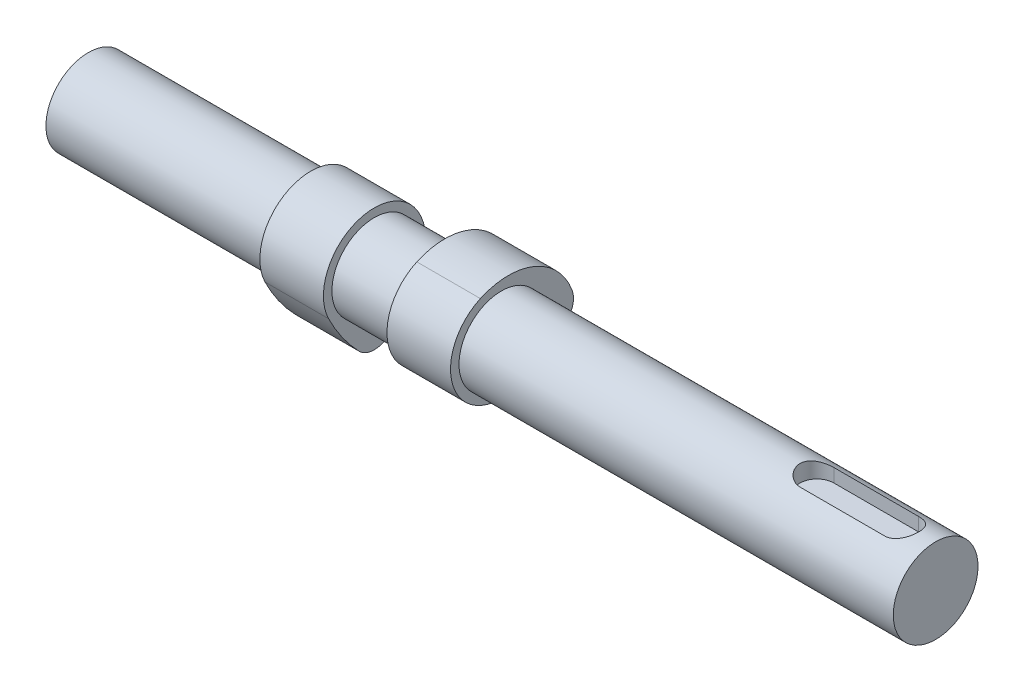
SolidWorks part; units mm, degrees
ref_plane "Ebene vorne" through (0, 0, 0) normal (0, 0, 1) x (1, 0, 0)
ref_plane "Ebene oben" through (0, 0, 0) normal (0, 1, 0) x (1, 0, 0)
ref_plane "Ebene rechts" through (0, 0, 0) normal (1, 0, 0) x (0, 0, -1)
sketch "Sketch1" plane through (0, 0, 0) normal (1, 0, 0) x (0, 0, -1)
  circle A0 centre (0, 0) radius 10
  dimension "D1" = 20
extrude "Boss-Extrude1" add sketch "Sketch1" against normal blind 75 and the other way blind 125
sketch "Sketch2" plane through (0, 0, 0) normal (1, 0, 0) x (0, 0, -1)
  line L0 (0, 0) -> (12.0293, 0) construction
  arc A0 (-4.9508, 10.9311) -> (5.2781, -10.7769) centre (0, 0) ccw
  arc A1 (15.5071, -3.5923) -> (16.747, 1.6562) centre (12.0293, 0) ccw
  arc A2 (-4.9508, 10.9311) -> (16.747, 1.6562) centre (1.6503, -3.6437) cw
  arc A3 (5.2781, -10.7769) -> (15.5071, -3.5923) centre (-12.3157, 25.1461) ccw
  point P3 (4.9629, -10.9257)
  point P8 (-0.945, 11.9627)
  dimension "D1" = 24
  dimension "D2" = 10
  dimension "D3" = 16
  dimension "D4" = 40
  dimension "D5" = 12.5
extrude "Boss-Extrude2" add sketch "Sketch2" along normal mid plane 15 from offset 15 separate body
mirror "Mirror4" about plane through (0, 0, 0) normal (1, 0, 0) of bodies 102
move or copy body "Body-Move/Copy1" bodies to move or copy 103 copy no rotation origin (0, 0, 0) rotation axis (-1, 0, 0) rotation angle 90
ref_plane "Plane1" through (0, 10, 0) normal (0, 1, 0) x (1, 0, 0)
sketch "Sketch3" plane through (0, 10, 0) normal (0, 1, 0) x (1, 0, 0)
  line L0 (125, 0) -> (73.1832, 0) construction
  line L1 (125, -10) -> (125, 10) construction
  line L2 (97, 0) -> (117, 0) construction
  line L3 (97, 4) -> (117, 4)
  line L4 (97, -4) -> (117, -4)
  arc A0 (97, 4) -> (97, -4) centre (97, 0) ccw
  arc A1 (117, -4) -> (117, 4) centre (117, 0) ccw
  point P7 (107, 0)
  dimension "D3" = 4
  dimension "D1" = 20
  dimension "D2" = 8
extrude "Cut-Extrude1" cut sketch "Sketch3" against normal blind 4
